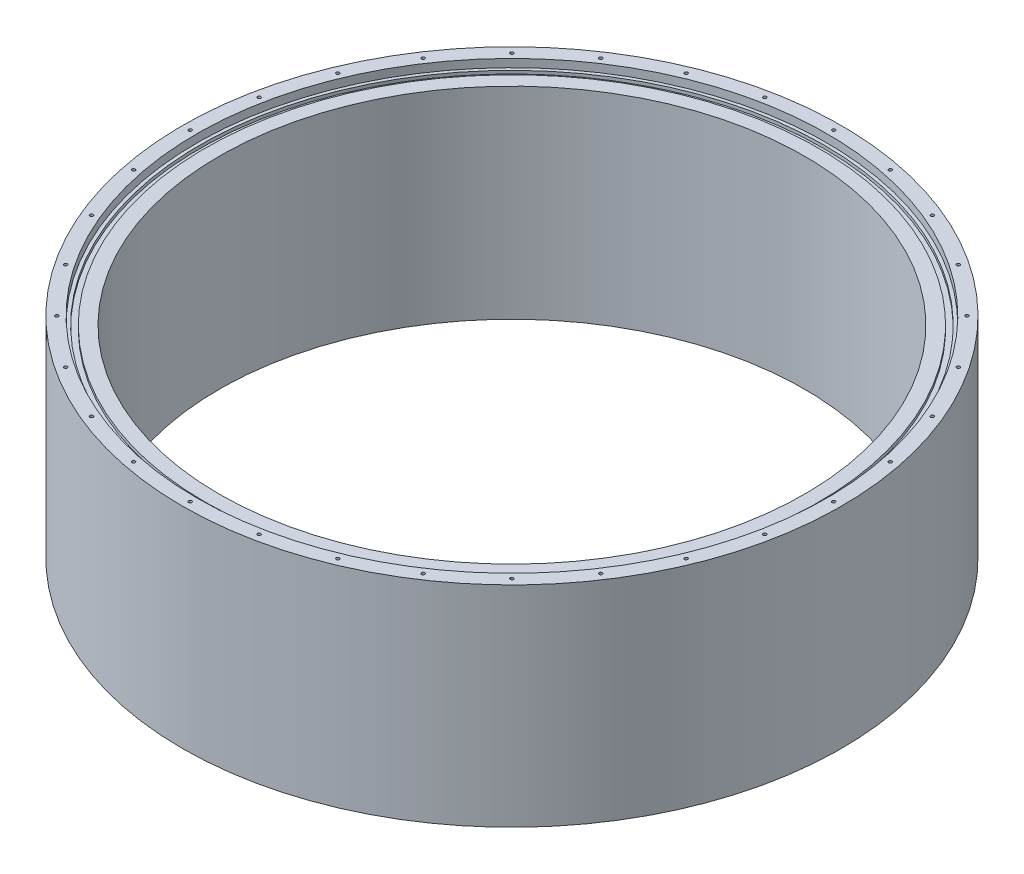
SolidWorks part; units mm, degrees
material "PVC Rigid"
ref_plane "Front" through (0, 0, 0) normal (0, 0, 1) x (1, 0, 0)
ref_plane "Top" through (0, 0, 0) normal (0, 1, 0) x (1, 0, 0)
ref_plane "Right" through (0, 0, 0) normal (1, 0, 0) x (0, 0, -1)
sketch "Sketch1" plane through (0, 0, 0) normal (0, 0, 1) x (1, 0, 0)
  line L0 (225.6, 74.685) -> (243, 74.685)
  line L1 (243, 74.685) -> (243, 80.885)
  line L2 (243, 80.885) -> (254, 80.885)
  line L3 (254, 80.885) -> (254, -80.885)
  line L4 (254, -80.885) -> (225.6, -80.885)
  line L5 (225.6, -80.885) -> (225.6, 74.685)
  line L6 (0, 80.885) -> (0, -80.885) construction
  line L7 (0, 0) -> (225.6, 0) construction
  dimension "D1" = 508
  dimension "D2" = 11
  dimension "D3" = 28.4
  dimension "D4" = 6.2
  dimension "D5" = 161.77
  dimension "D6" = 225.6
  dimension "D7" = 155.57
revolve "Revolve1" add sketch "Sketch1" angle 360 about L6
sketch "Sketch2" plane through (0, 0, 0) normal (0, 0, 1) x (1, 0, 0)
  line L0 (0, 80.885) -> (0, -80.885) construction
  line L1 (254, 80.885) -> (-254, 80.885) construction
  line L2 (-254, -80.885) -> (254, -80.885) construction
  line L3 (240.5, 72.272) -> (240.5, -77.587) construction
  line L4 (236.3344, 74.685) -> (240.5, 74.685)
  line L5 (236.3344, 74.685) -> (236.3344, 72.272)
  line L6 (236.3344, 72.272) -> (240.5, 72.272)
  line L7 (240.5, 74.685) -> (240.5, 72.272)
  line L8 (225.6, 74.685) -> (-225.6, 74.685) construction
  line L9 (225.6, 74.685) -> (-225.6, 74.685) construction
  line L10 (254, -80.885) -> (254, 80.885) construction
  line L12 (236.3344, -78.472) -> (240.5, -78.472) construction
  line L13 (236.3344, -78.472) -> (236.3344, -80.885) construction
  line L14 (236.3344, -80.885) -> (240.5, -80.885) construction
  line L15 (240.5, -78.472) -> (240.5, -80.885) construction
  dimension "D1" = 13.5
  dimension "D2" = 2.413
  dimension "D3" = 4.1656
revolve "Cut-Revolve1" cut sketch "Sketch2" angle 360 about L0
hole_wizard "M3x0.5 Tapped Hole1" positions "Sketch3" profile "Sketch4" tap size "M3x0.5" standard "ANSI Metric"
sketch "Sketch3" plane through (0, 80.885, 0) normal (0, 1, 0) x (1, 0, 0)
  point P0 (248, 0)
  dimension "D1" = 248
sketch "Sketch4" plane through (248, 80.885, 0) normal (1, 0, 0) x (0, 0, 1)
  line L0 (0, 0) -> (0, 10.2511)
  line L1 (0, 10.2511) -> (1.25, 9.5)
  line L2 (1.25, 9.5) -> (1.25, 0)
  line L5 (1.25, 0) -> (0, 0)
  line L10 (0, 10.2511) -> (-1.25, 9.5) construction
  line L11 (0, -6.35) -> (0, 107.95) construction
  dimension "Tap Drill Dia." = 2.5
  dimension "Tap Drill Depth" = 9.5
  dimension "Drill Angle" = 118
cosmetic thread "Hole Thread1" parameters "D1"=8, "D2"=3
pattern_circular "CirPattern1" count 32 over 360 about axis through (0, 0, 0) along (0, 1, 0) of "M3x0.5 Tapped Hole1"
mirror "Mirror1" about plane through (0, 0, 0) normal (0, 1, 0) of "CirPattern1", "M3x0.5 Tapped Hole1"
hole_wizard "Ø5.0mm Dowel Hole1" positions "Sketch5" profile "Sketch6" hole size "Ø5.0" standard "ANSI Metric"
sketch "Sketch5" plane through (0, -80.885, 0) normal (0, -1, 0) x (-1, 0, 0)
  line L2 (0, 0) -> (0, 204.5498) construction
  line L3 (-24.2102, 245.8106) -> (0, 0) construction
  line L4 (0, 0) -> (24.9245, -253.0623) construction
  circle A1 centre (0, 0) radius 247
  point P6 (-24.2102, 245.8106)
  point P8 (24.2102, -245.8106)
  dimension "D2" = 494
  dimension "D1" = 5.625
sketch "Sketch6" plane through (-24.2102, -80.885, 245.8106) normal (1, 0, 0) x (0, 0, -1)
  line L0 (0, 0) -> (0, 21.0172)
  line L1 (0, 21.0172) -> (2.525, 19.5)
  line L2 (2.525, 19.5) -> (2.525, 0)
  line L5 (2.525, 0) -> (0, 0)
  line L10 (0, 21.0172) -> (-2.525, 19.5) construction
  line L11 (0, -6.35) -> (0, 107.95) construction
  dimension "Hole Dia." = 5.05
  dimension "Hole Depth" = 19.5
  dimension "Drill Angle" = 118
